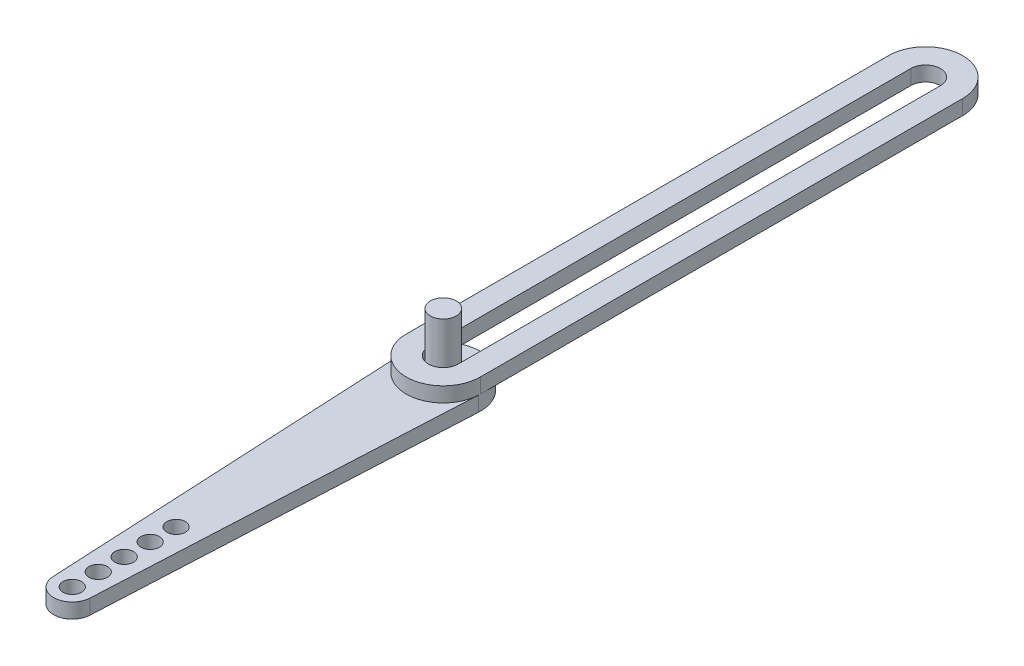
SolidWorks part; units mm, degrees
ref_plane "Front Plane" through (0, 0, 0) normal (0, 0, 1) x (1, 0, 0)
ref_plane "Top Plane" through (0, 0, 0) normal (0, 1, 0) x (1, 0, 0)
ref_plane "Right Plane" through (0, 0, 0) normal (1, 0, 0) x (0, 0, -1)
sketch "Sketch1" plane through (0, 0, 0) normal (0, 1, 0) x (1, 0, 0)
  circle A0 centre (0, 0) radius 3.5
  dimension "D1" = 7
extrude "Boss-Extrude1" add sketch "Sketch1" against normal blind 15
sketch "Sketch2" plane through (0, -15, 0) normal (0, -1, 0) x (1, 0, 0)
  line L0 (0, 0) -> (0, 100) construction
  line L1 (9.9875, 0.5) -> (4.9937, 100.25)
  line L2 (-9.9875, 0.5) -> (-4.9937, 100.25)
  arc A0 (-9.9875, 0.5) -> (9.9875, 0.5) centre (0, 0) ccw
  arc A1 (4.9937, 100.25) -> (-4.9937, 100.25) centre (0, 100) ccw
  dimension "D1" = 20
  dimension "D2" = 10
  dimension "D3" = 100
extrude "Boss-Extrude2" add sketch "Sketch2" along normal blind 4
sketch "Sketch3" plane through (0, -19, 0) normal (0, -1, 0) x (1, 0, 0)
  line L0 (52.5393, 104.215) -> (52.5393, -5.785)
  line L1 (0, 100) -> (0, 0) construction
  circle A0 centre (0, 100) radius 2.5
  dimension "D2" = 5
  dimension "D1" = 110
extrude "Cut-Extrude1" cut sketch "Sketch3" against normal through all contours A0
pattern_linear "LPattern1" count 5 spacing 7 along (0, 0, -1) of "Cut-Extrude1"
sketch "Sketch4" plane through (0, -15, 0) normal (0, 1, 0) x (1, 0, 0)
  line L0 (0, 0) -> (0, 130) construction
  line L1 (-10, 0) -> (-10, 130)
  line L2 (10, 0) -> (10, 130)
  line L3 (0, 0) -> (0, 130) construction
  line L4 (-4, 0) -> (-4, 130)
  line L5 (4, 0) -> (4, 130)
  arc A0 (-10, 0) -> (10, 0) centre (0, 0) ccw
  arc A1 (10, 130) -> (-10, 130) centre (0, 130) ccw
  arc A2 (-4, 0) -> (4, 0) centre (0, 0) ccw
  arc A3 (4, 130) -> (-4, 130) centre (0, 130) ccw
  point P4 (0, 65)
  point P9 (0, 65)
  dimension "D2" = 10
  dimension "D3" = 4
  dimension "D1" = 130
extrude "Boss-Extrude3" add sketch "Sketch4" along normal blind 4
sketch "Sketch5" plane through (0, -19, 0) normal (0, -1, 0) x (1, 0, 0)
  circle A0 centre (0, 0) radius 6.5
  dimension "D1" = 13
extrude "Boss-Extrude4" add sketch "Sketch5" along normal blind 2
